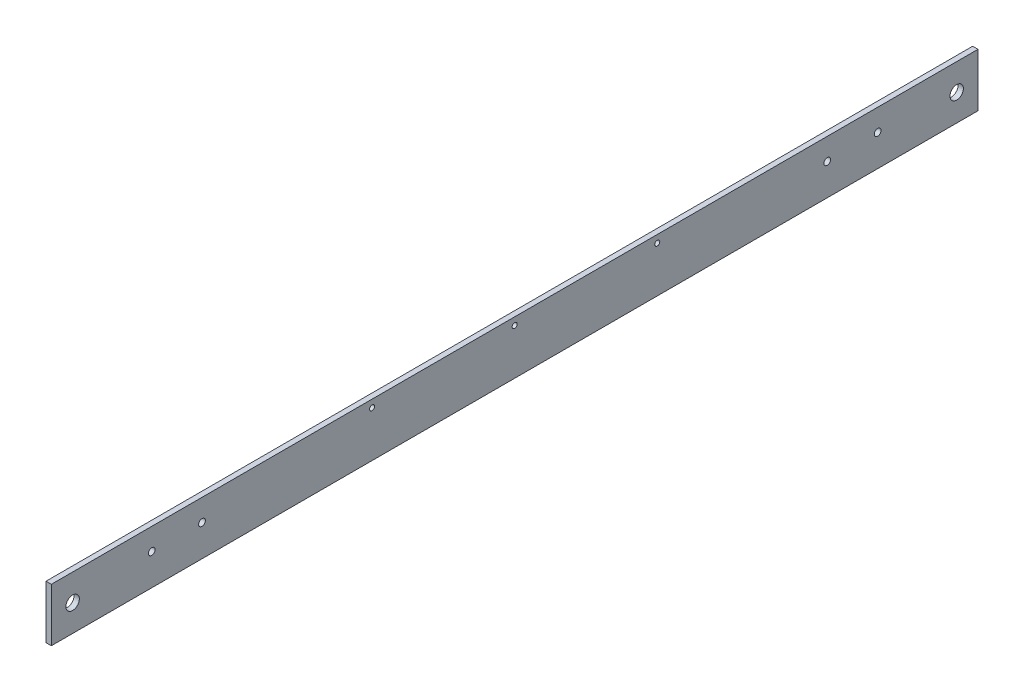
SolidWorks part; units mm, degrees
ref_plane "Front Plane" through (0, 0, 0) normal (0, 0, 1) x (1, 0, 0)
ref_plane "Top Plane" through (0, 0, 0) normal (0, 1, 0) x (1, 0, 0)
ref_plane "Right Plane" through (0, 0, 0) normal (1, 0, 0) x (0, 0, -1)
sketch "Sketch1" plane through (0, 0, 0) normal (1, 0, 0) x (0, 0, -1)
  line L1 (0, 0) -> (552.45, 0)
  line L2 (0, 0) -> (0, 31.75)
  line L3 (0, 31.75) -> (552.45, 31.75)
  line L4 (552.45, 0) -> (552.45, 31.75)
  circle A0 centre (12.7, 15.875) radius 4
  circle A1 centre (539.75, 15.875) radius 4
  circle A2 centre (462.625, 18.75) radius 2
  circle A3 centre (492.625, 18.75) radius 2
  circle A4 centre (59.825, 18.75) radius 2
  circle A5 centre (89.825, 18.75) radius 2
  dimension "D3" = 8
  dimension "D7" = 4
  dimension "D1" = 31.75
  dimension "D2" = 552.45
  dimension "D4" = 15.875
  dimension "D5" = 12.7
  dimension "D6" = 12.7
  dimension "D8" = 30
  dimension "D10" = 13
  dimension "D9" = 59.825
  dimension "D11" = 462.625
  dimension "D12" = 492.625
  dimension "D13" = 59.825
  dimension "D14" = 30
extrude "Boss-Extrude2" add sketch "Sketch1" along normal blind 3.175
sketch "Sketch2" plane through (3.175, 0, 0) normal (1, 0, 0) x (0, 0, -1)
  line L0 (0, 31.75) -> (0, 0) construction
  line L1 (552.45, 31.75) -> (0, 31.75) construction
  circle A0 centre (191.225, 27.25) radius 1.5
  circle A1 centre (276.225, 27.25) radius 1.5
  circle A2 centre (361.225, 27.25) radius 1.5
  dimension "D4" = 3
  dimension "D1" = 170
  dimension "D2" = 85
  dimension "D3" = 191.225
  dimension "D5" = 4.5
extrude "LightingGuideMountHolesCut-Extrude1" cut sketch "Sketch2" against normal through all
equation "\"RailThickness\"= .125in'Spec"
equation "\"VSWidth\"= 1.25in'Spec"
equation "\"SideRailLength\"= 21.75in"
equation "\"StepperHolePadSize\"= \"StepperHoleDiameter\""
equation "\"D1@Sketch1\"=\"TopRailHeight\""
equation "\"D2@Sketch1\"=\"SideRailLength\""
equation "\"FrameFastenerHoleDiameter\"= 8mm"
equation "\"D3@Sketch1\"=\"FrameFastenerHoleDiameter\""
equation "\"D4@Sketch1\"=\"TopRailHeight\"/2"
equation "\"D5@Sketch1\"=\"FrameFastenerHoleOffsetFromEdge\""
equation "\"D6@Sketch1\"=\"FrameFastenerHoleOffsetFromEdge\""
equation "\"D1@Boss-Extrude2\"=\"RailThickness\""
equation "\"FrameFastenerHoleOffsetFromEdge\"= \"VSWidth\" / 2 - \"GapBetweenVerticalSupportsAndRails\" / 2"
equation "\"TopRailHeight\"= 1.25in"
equation "\"GapBetweenVerticalSupportsAndRails\"= \"RailThickness\" * 2"
equation "\"AngleBracketSmallHoleDiameter\"= 4mm"
equation "\"AngleBracketSlotDistanceBetweenHoles\"= 30mm"
equation "\"AngleBracketSlotDistanceFromTop\"= 13mm"
equation "\"AngleBracketSlotDistanceFromCorner\"= \"AngleBracketSlotDistanceFromBack\" - \"GapBetweenVerticalSupportsAndRails\" / 2'Equals 61.825"
equation "\"D7@Sketch1\"=\"AngleBracketSmallHoleDiameter\""
equation "\"D8@Sketch1\"=\"AngleBracketSlotDistanceBetweenHoles\""
equation "\"D10@Sketch1\"=\"AngleBracketSlotDistanceFromTop\""
equation "\"D9@Sketch1\"= \"AngleBracketSlotDistanceFromCorner\" - 2mm 'Minus 2mm to get screw hole in middle of slot"
equation "\"AngleBracketSlotDistanceFromBack\"= 65mm"
equation "\"D13@Sketch1\"= \"AngleBracketSlotDistanceFromCorner\" - 2mm'Minus 2mm to get screw hole in middle of slot"
equation "\"D14@Sketch1\"=\"AngleBracketSlotDistanceBetweenHoles\""
equation "\"D3@Sketch2\"=(\"SideRailLength\" -\"LightStripLength\" + \"LightStripGuideMountingHoleFromLeftOrRightSide\"*2)/2"
equation "\"LightStripLength\"= 270mm'Spec"
equation "\"LightStripGuideMountingHoleFromLeftOrRightSide\"= 50mm"
equation "\"M3HoleDiameter\"= 3mm"
equation "\"D1@Sketch2\"=\"LightStripLength\" - \"LightStripGuideMountingHoleFromLeftOrRightSide\"*2"
equation "\"D2@Sketch2\"=(\"LightStripLength\"-\"LightStripGuideMountingHoleFromLeftOrRightSide\"*2)/2"
equation "\"D4@Sketch2\"=\"M3HoleDiameter\""
equation "\"LightStripGuideMountingHoleFromTop\"= 4.5mm"
equation "\"D5@Sketch2\"=\"LightStripGuideMountingHoleFromTop\""
